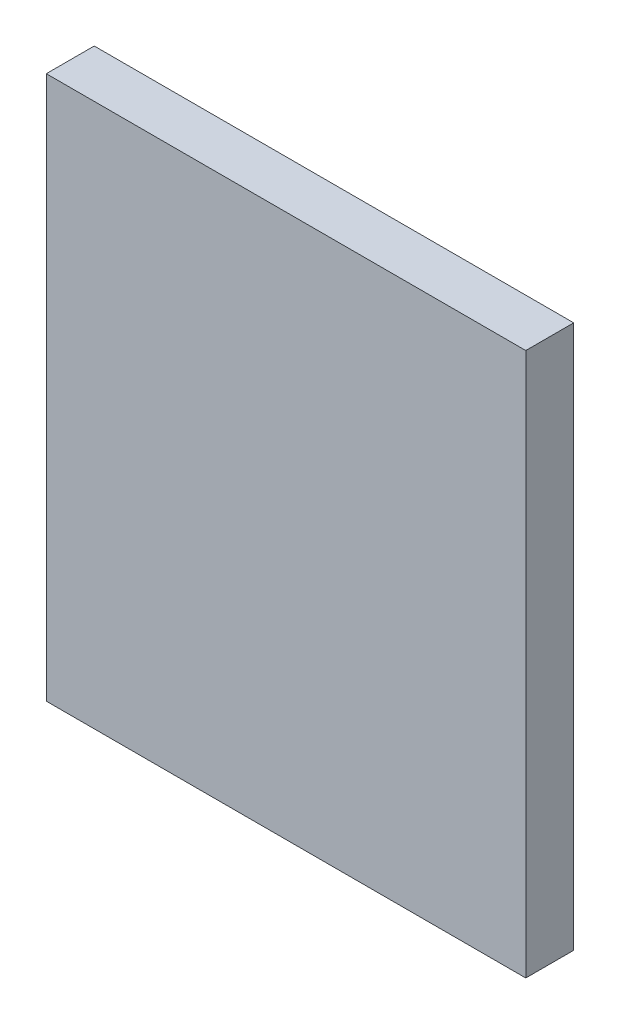
SolidWorks part; units mm, degrees
ref_plane "前视基准面" through (0, 0, 0) normal (0, 0, 1) x (1, 0, 0)
ref_plane "上视基准面" through (0, 0, 0) normal (0, 1, 0) x (1, 0, 0)
ref_plane "右视基准面" through (0, 0, 0) normal (1, 0, 0) x (0, 0, -1)
sketch "草图1" plane through (0, 0, 0) normal (0, 0, 1) x (1, 0, 0)
  line L0 (0, 0) -> (0, 85) construction
  line L1 (-75, 85) -> (75, 85)
  line L2 (-75, 85) -> (-75, -85)
  line L3 (-75, -85) -> (75, -85)
  line L4 (75, 85) -> (75, -85)
  line L5 (-75, 85) -> (75, -85) construction
  line L6 (-75, -85) -> (75, 85) construction
  point P0 (0, 0)
extrude "凸台-拉伸1" add sketch "草图1" along normal blind 15
